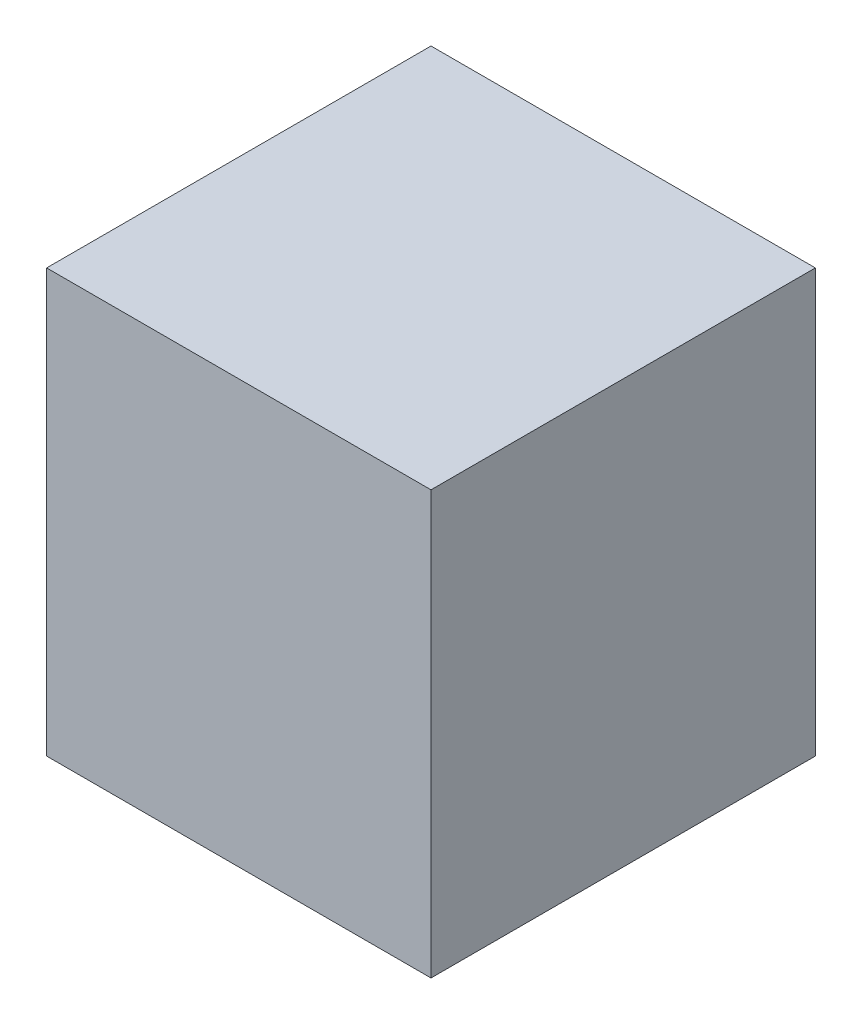
SolidWorks part; units mm, degrees
ref_plane "Front Plane" through (0, 0, 0) normal (0, 0, 1) x (1, 0, 0)
ref_plane "Top Plane" through (0, 0, 0) normal (0, 1, 0) x (1, 0, 0)
ref_plane "Right Plane" through (0, 0, 0) normal (1, 0, 0) x (0, 0, -1)
sketch "Sketch1" plane through (0, 0, 0) normal (0, 1, 0) x (1, 0, 0)
  line L1 (5, -5) -> (-5, -5)
  line L2 (5, -5) -> (5, 5)
  line L3 (5, 5) -> (-5, 5)
  line L4 (-5, -5) -> (-5, 5)
  line L5 (5, -5) -> (-5, 5) construction
  line L6 (5, 5) -> (-5, -5) construction
  point P0 (0, 0)
  dimension "D1" = 10
  dimension "D2" = 10
extrude "Boss-Extrude1" add sketch "Sketch1" along normal blind 11
